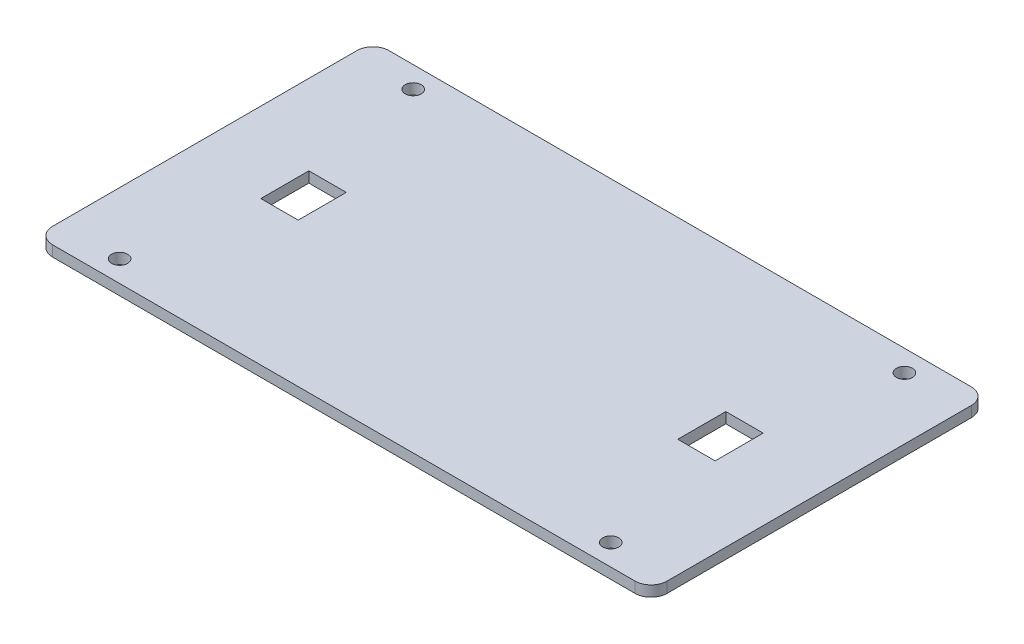
SolidWorks part; units mm, degrees
ref_plane "Plano frontal" through (0, 0, 0) normal (0, 0, 1) x (1, 0, 0)
ref_plane "Plano superior" through (0, 0, 0) normal (0, 1, 0) x (1, 0, 0)
ref_plane "Plano direito" through (0, 0, 0) normal (1, 0, 0) x (0, 0, -1)
sketch "Esboço1" plane through (0, 0, 0) normal (0, 1, 0) x (1, 0, 0)
  line L7 (-57.5484, 31.5) -> (57.5484, 31.5)
  line L8 (57.5484, 31.5) -> (57.5484, -31.5)
  line L9 (57.5484, -31.5) -> (-57.5484, -31.5)
  line L10 (-57.5484, -31.5) -> (-57.5484, 31.5)
  line L11 (0, 31.5) -> (0, -31.5) construction
  line L12 (-57.5484, 0) -> (57.5484, 0) construction
  dimension "D1" = 63
  dimension "D2" = 115.0968
extrude "Ressalto-extrusão1" add sketch "Esboço1" along normal blind 2
fillet "Filete1" radius 3 4 edges at (57.5484, 1, -31.5) (57.5484, 1, 31.5) (-57.5484, 1, 31.5) (-57.5484, 1, -31.5)
sketch "Esboço6" plane through (0, 2, 0) normal (0, 1, 0) x (1, 0, 0)
  line L0 (-57.5484, 0) -> (57.5484, 0) construction
  line L1 (-57.5484, 28.5) -> (-57.5484, -28.5) construction
  line L2 (57.5484, -28.5) -> (57.5484, 28.5) construction
  line L3 (-42.5484, -4.5) -> (-42.5484, 4.5)
  line L4 (-42.5484, 4.5) -> (-35.5484, 4.5)
  line L5 (-35.5484, 4.5) -> (-35.5484, -4.5)
  line L6 (-35.5484, -4.5) -> (-42.5484, -4.5)
  line L7 (0, -31.5) -> (0, 31.5) construction
  line L8 (-54.5484, -31.5) -> (54.5484, -31.5) construction
  line L9 (54.5484, 31.5) -> (-54.5484, 31.5) construction
  line L10 (35.5484, -4.5) -> (42.5484, -4.5)
  line L11 (35.5484, 4.5) -> (35.5484, -4.5)
  line L12 (42.5484, 4.5) -> (35.5484, 4.5)
  line L13 (42.5484, -4.5) -> (42.5484, 4.5)
  point P9 (-42.5484, 0)
  point P21 (42.5484, 0)
  dimension "D1" = 9
  dimension "D2" = 7
  dimension "D3" = 15
extrude "Corte-extrusão4" cut sketch "Esboço6" against normal through all and the other way through all
sketch "Esboço7" plane through (0, 2, 0) normal (0, 1, 0) x (1, 0, 0)
  line L0 (54.5484, 31.5) -> (-54.5484, 31.5) construction
  line L1 (-57.5484, 28.5) -> (-57.5484, -28.5) construction
  line L2 (0, 0) -> (0, 31.5) construction
  line L3 (0, 0) -> (57.5484, 0) construction
  line L4 (57.5484, -28.5) -> (57.5484, 28.5) construction
  circle A0 centre (-45.9984, 27.5) radius 1.5
  circle A1 centre (45.9984, 27.5) radius 1.5
  circle A2 centre (45.9984, -27.5) radius 1.5
  circle A3 centre (-45.9984, -27.5) radius 1.5
  dimension "D1" = 3
  dimension "D2" = 4
  dimension "D3" = 11.55
extrude "Corte-extrusão5" cut sketch "Esboço7" against normal through all
